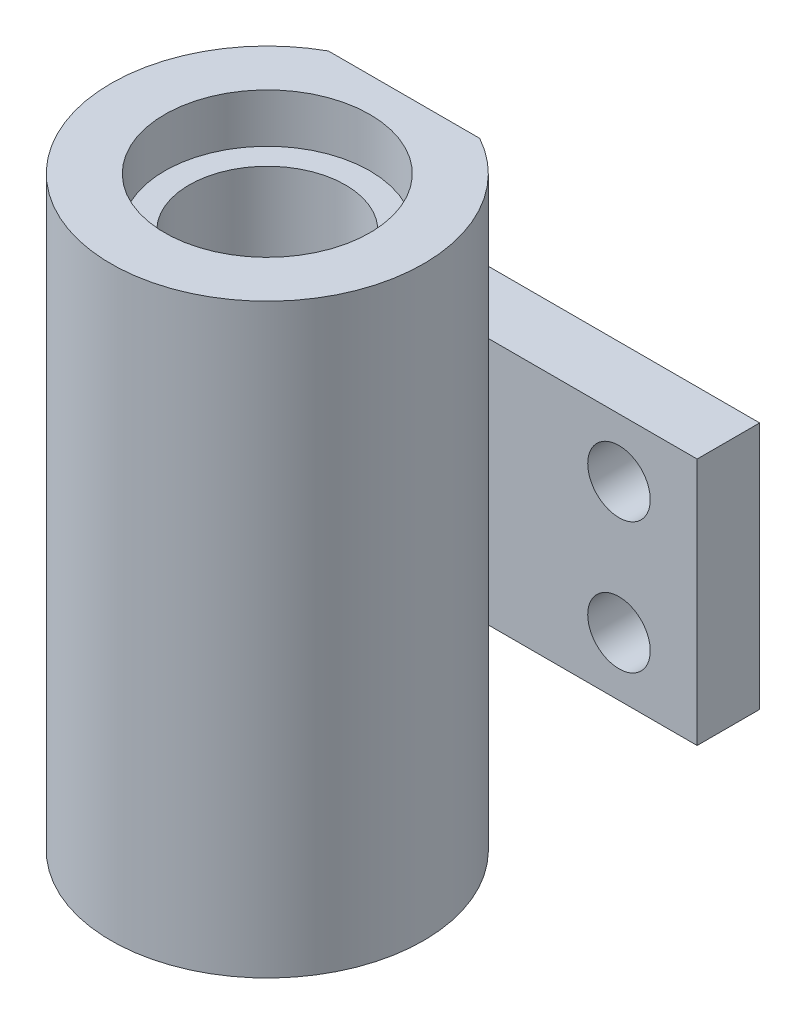
SolidWorks part; units mm, degrees
ref_plane "Alzado" through (0, 0, 0) normal (0, 0, 1) x (1, 0, 0)
ref_plane "Planta" through (0, 0, 0) normal (0, 1, 0) x (1, 0, 0)
ref_plane "Vista lateral" through (0, 0, 0) normal (1, 0, 0) x (0, 0, -1)
sketch "Croquis1" plane through (0, 0, 0) normal (0, 0, 1) x (1, 0, 0)
  line L0 (0, 0) -> (0, 61.286) construction
  line L1 (-8, 55) -> (-10.5, 55)
  line L2 (-10.5, 55) -> (-10.5, 60)
  line L3 (-10.5, 60) -> (-16, 60)
  line L4 (-16, 60) -> (-16, 0)
  line L5 (-16, 0) -> (-10.5, 0)
  line L6 (-10.5, 0) -> (-10.5, 5)
  line L7 (-10.5, 5) -> (-8, 5)
  line L8 (-8, 5) -> (-8, 55)
  dimension "D1" = 60
  dimension "D2" = 16
  dimension "D3" = 21
  dimension "D4" = 32
  dimension "D5" = 5
  dimension "D6" = 5
  dimension "D7" = 5.5
revolve "Revolución1" add sketch "Croquis1" angle 360 about L0
sketch "Croquis2" plane through (0, 0, 0) normal (0, -1, 0) x (1, 0, 0)
  line L0 (0, 0) -> (0, -33.7888) construction
  line L1 (-15, -24) -> (15, -24)
  line L2 (-15, -24) -> (-15, -14)
  line L3 (-15, -14) -> (15, -14)
  line L4 (15, -24) -> (15, -14)
  line L5 (-7.746, -16) -> (17.9207, -16) construction
  line L6 (-7.746, -14) -> (-7.746, -16) construction
  line L7 (17.9207, -14) -> (17.9207, -16) construction
  circle A0 centre (0, 0) radius 16 construction
  dimension "D1" = 14
  dimension "D2" = 10
  dimension "D3" = 25.6666
  dimension "D5" = 30
  dimension "D6" = 15
extrude "Cortar-Extruir1" cut sketch "Croquis2" against normal blind 64
sketch "Croquis3" plane through (0, 0, -14) normal (0, 0, -1) x (-1, 0, 0)
  line L0 (0, 60) -> (0, 0) construction
  line L1 (-7.746, 60) -> (7.746, 60) construction
  line L3 (-30, 17.3) -> (30, 17.3)
  line L4 (-30, 17.3) -> (-30, 42.7)
  line L5 (-30, 42.7) -> (30, 42.7)
  line L6 (30, 17.3) -> (30, 42.7)
  line L7 (-30, 17.3) -> (30, 42.7) construction
  line L8 (-30, 42.7) -> (30, 17.3) construction
  line L9 (-22, 36.7) -> (22, 36.7) construction
  line L10 (-22, 36.7) -> (-22, 23.3) construction
  line L11 (-22, 23.3) -> (22, 23.3) construction
  line L12 (22, 36.7) -> (22, 23.3) construction
  circle A0 centre (-22, 36.7) radius 3.2
  circle A1 centre (-22, 23.3) radius 3.2
  circle A2 centre (22, 36.7) radius 3.2
  circle A3 centre (22, 23.3) radius 3.2
  point P5 (0, 30)
  dimension "D3" = 6.4
  dimension "D4" = 8
  dimension "D5" = 6
  dimension "D1" = 25.4
  dimension "D2" = 60
  dimension "D6" = 8
  dimension "D7" = 6
  dimension "D8" = 6
extrude "Saliente-Extruir1" add sketch "Croquis3" along normal blind 6.4
